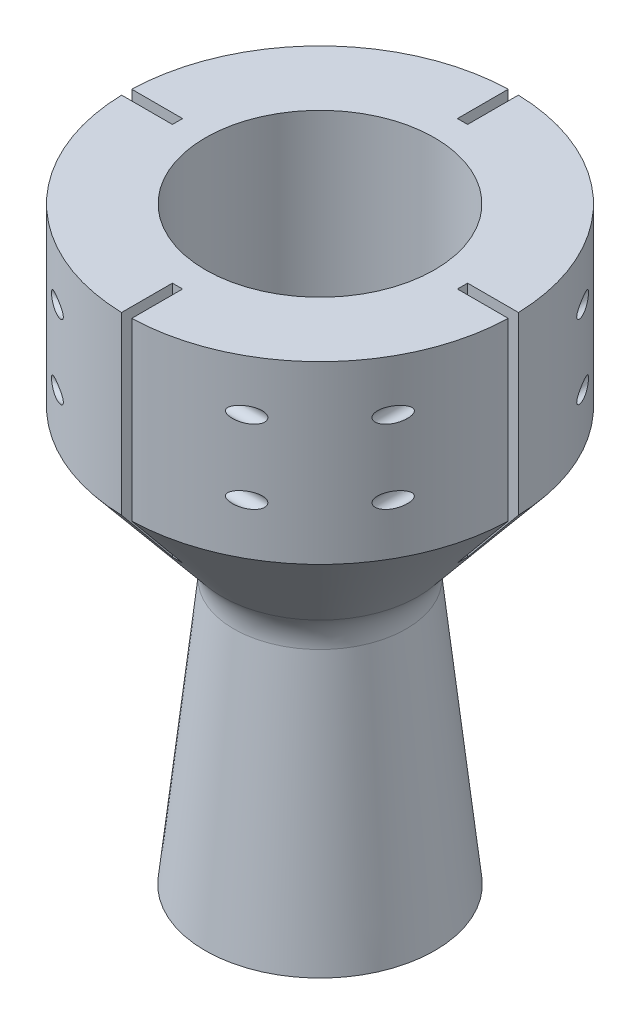
SolidWorks part; units mm, degrees
ref_plane "Front Plane" through (0, 0, 0) normal (0, 0, 1) x (1, 0, 0)
ref_plane "Top Plane" through (0, 0, 0) normal (0, 1, 0) x (1, 0, 0)
ref_plane "Right Plane" through (0, 0, 0) normal (1, 0, 0) x (0, 0, -1)
sketch "Sketch1" plane through (0, 0, 0) normal (0, 1, 0) x (1, 0, 0)
  circle A0 centre (0, 0) radius 22.5
  circle A1 centre (0, 0) radius 38
  circle A2 centre (0, 0) radius 40 construction
extrude "Boss-Extrude1" add sketch "Sketch1" along normal blind 34.5
sketch "Sketch2" plane through (0, 0, 0) normal (0, -1, 0) x (1, 0, 0)
  line L0 (22.5, 0) -> (38, 0) construction
  line L1 (0, 0) -> (0, 38) construction
ref_plane "Plane1" through (0, 0, 0) normal (0, 0, 1) x (1, 0, 0)
sketch "Sketch3" plane through (0, 0, 0) normal (0, 0, 1) x (1, 0, 0)
  line L0 (-38, 0) -> (-19.2302, -22.7532)
  line L1 (-16.9475, -29.3747) -> (-22.5541, -81.3132)
  line L3 (-22.5541, -81.3132) -> (-18.5541, -81.3132)
  line L4 (-18.5541, -81.3132) -> (-13.8591, -31.5341)
  line L5 (-15.6594, -18.123) -> (-22.5, 0)
  line L6 (-22.5, 0) -> (-38, 0)
  line L7 (0, 0) -> (0, 43.8983) construction
  arc A0 (-16.9475, -29.3747) -> (-19.2302, -22.7532) centre (-26.9442, -29.1167) ccw
  arc A1 (-13.8591, -31.5341) -> (-15.6594, -18.123) centre (-43.7265, -28.7171) ccw
  point P14 (-13.207, -24.6202)
  dimension "D1" = 10
  dimension "D2" = 30
revolve "Revolve1" add sketch "Sketch3" angle 360 about L7
sketch "Sketch4" plane through (0, 34.5, 0) normal (0, 1, 0) x (1, 0, 0)
  line L0 (0, 0) -> (0, 30.5656) construction
  line L1 (0, 38) -> (16.3696, 38) construction
  line L2 (-1, 48) -> (1, 48)
  line L3 (-1, 48) -> (-1, 28)
  line L4 (-1, 28) -> (1, 28)
  line L5 (1, 48) -> (1, 28)
  line L6 (-1, 48) -> (1, 28) construction
  line L7 (-1, 28) -> (1, 48) construction
  line L8 (48, 1) -> (28, 1)
  line L9 (48, 1) -> (48, -1)
  line L10 (48, -1) -> (28, -1)
  line L11 (28, 1) -> (28, -1)
  line L12 (1, -48) -> (1, -28)
  line L13 (1, -48) -> (-1, -48)
  line L14 (-1, -48) -> (-1, -28)
  line L15 (1, -28) -> (-1, -28)
  line L16 (-48, -1) -> (-28, -1)
  line L17 (-48, -1) -> (-48, 1)
  line L18 (-48, 1) -> (-28, 1)
  line L19 (-28, -1) -> (-28, 1)
  circle A0 centre (0, 0) radius 38 construction
  point P1 (0, 38)
  point P27 (0, 0)
  dimension "D1" = 10
  dimension "D2" = 2
  dimension "D3" = 4
extrude "Cut-Extrude1" cut sketch "Sketch4" against normal through all
ref_plane "Plane2" through (0, 0, 0) normal (1, 0, 0) x (0, 0, -1)
sketch "Sketch5" plane through (0, 0, 0) normal (1, 0, 0) x (0, 0, -1)
  line L0 (37.9868, 34.5) -> (37.9868, 56.9345) construction
  line L1 (33, 43.4774) -> (33, 27.7526) construction
  line L3 (37.9868, 34.5) -> (1, 34.5) construction
  line L4 (200000, 0) -> (-200038, 0) construction
  line L5 (0, -81.3132) -> (0, 95.3243) construction
  circle A0 centre (33, 24.5) radius 1.5
  circle A1 centre (33, 10) radius 1.5
  circle A2 centre (-33, 10) radius 1.5
  circle A3 centre (-33, 24.5) radius 1.5
  dimension "D2" = 10
  dimension "D3" = 10
  dimension "D1" = 4.9868
extrude "Cut-Extrude2" cut sketch "Sketch5" against normal through all and the other way through all
sketch "Sketch6" plane through (0, 0, 0) normal (0, 0, 1) x (1, 0, 0)
  line L0 (-37.9868, 34.5) -> (-37.9868, 54.0799) construction
  line L1 (-32.9868, 34.5) -> (-32.9868, 51.4396) construction
  line L3 (-1, 34.5) -> (-37.9868, 34.5) construction
  line L4 (-199977.5, 0) -> (200038, 0) construction
  line L5 (0, -8.6988) -> (0, 53.2976) construction
  circle A0 centre (-32.9868, 24.5) radius 1.5
  circle A1 centre (-32.9868, 10) radius 1.5
  circle A2 centre (32.9868, 10) radius 1.5
  circle A3 centre (32.9868, 24.5) radius 1.5
  dimension "D2" = 10
  dimension "D1" = 5
  dimension "D3" = 10
extrude "Cut-Extrude3" cut sketch "Sketch6" against normal through all and the other way through all
